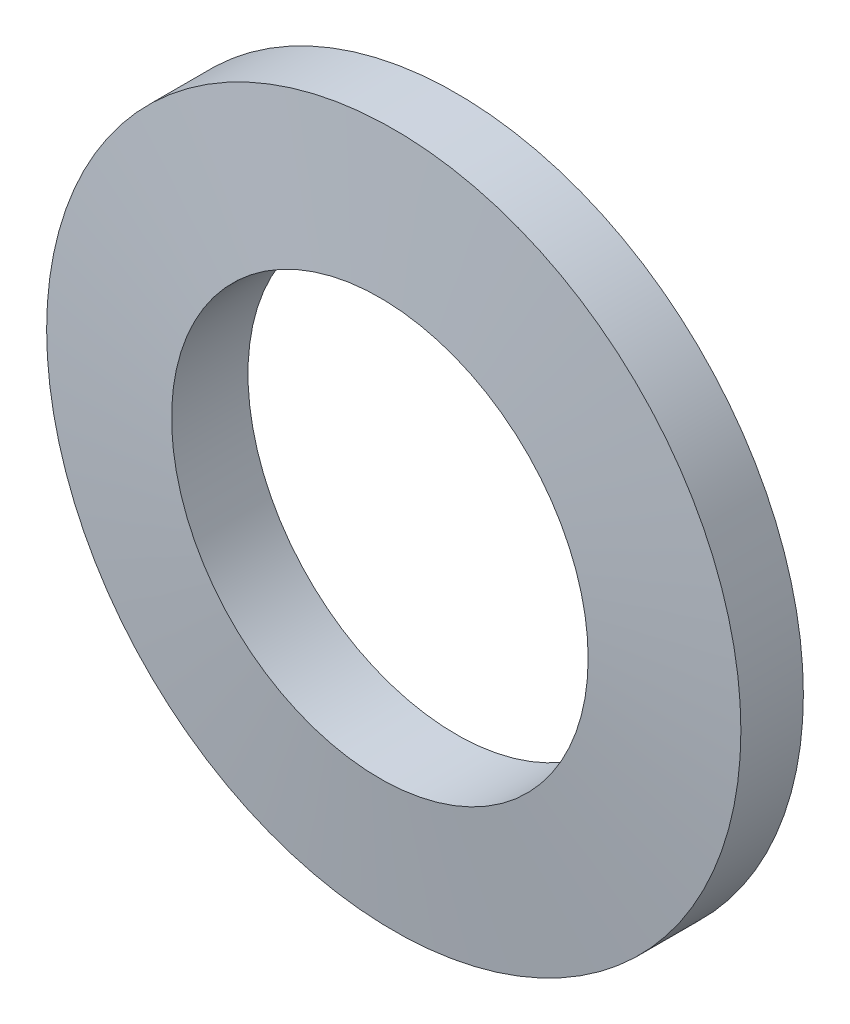
SolidWorks part; units mm, degrees
ref_plane "Front Plane" through (0, 0, 0) normal (0, 0, 1) x (1, 0, 0)
ref_plane "Top Plane" through (0, 0, 0) normal (0, 1, 0) x (1, 0, 0)
ref_plane "Right Plane" through (0, 0, 0) normal (1, 0, 0) x (0, 0, -1)
sketch "Sketch1" plane through (0, 0, 0) normal (1, 0, 0) x (0, 0, -1)
  line L0 (0, 30) -> (11, 30)
  line L1 (11, 30) -> (11, 50)
  line L2 (11, 50) -> (2, 50)
  line L3 (2, 50) -> (0, 30)
  line L4 (0, 0) -> (56.6009, 0) construction
  line L5 (0, 30) -> (0, 0) construction
  dimension "D1" = 100
  dimension "D2" = 60
  dimension "D3" = 11
  dimension "D4" = 9
revolve "Revolve1" add sketch "Sketch1" angle 360 about L4
